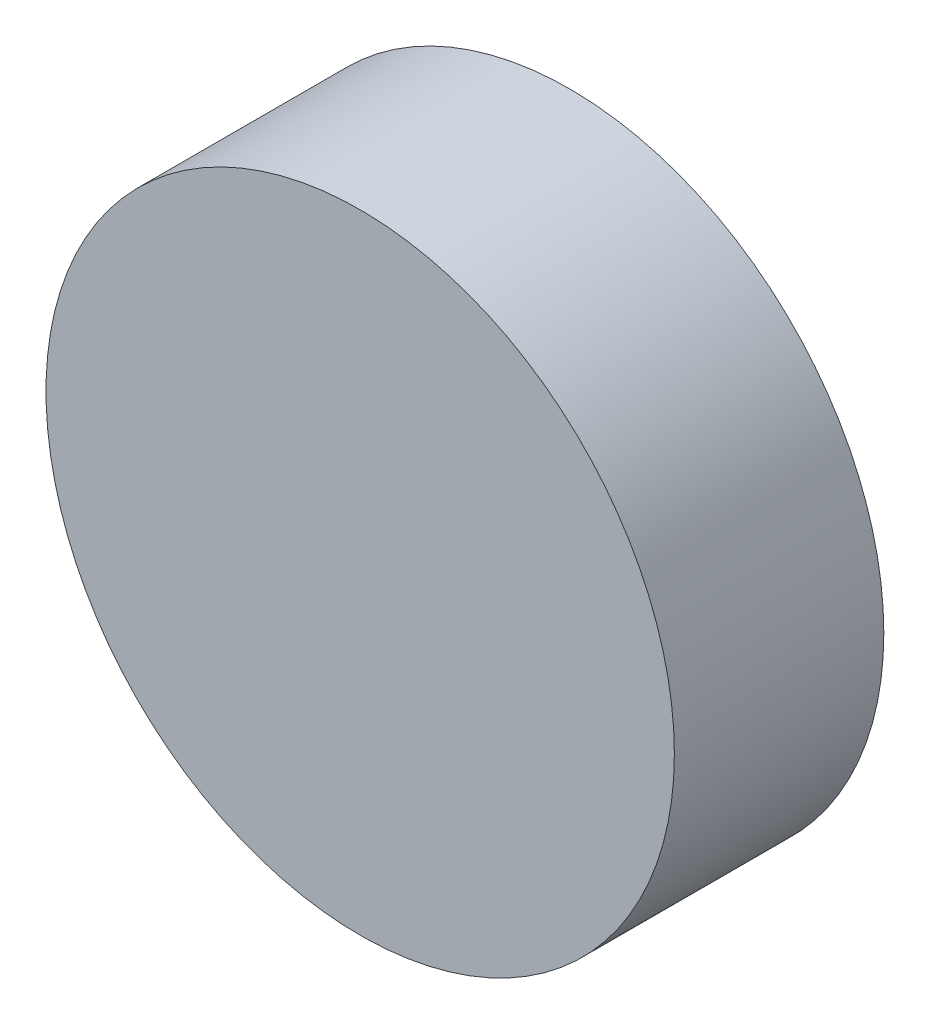
SolidWorks part; units mm, degrees
ref_plane "正面" through (0, 0, 0) normal (0, 0, 1) x (1, 0, 0)
ref_plane "平面" through (0, 0, 0) normal (0, 1, 0) x (1, 0, 0)
ref_plane "右側面" through (0, 0, 0) normal (1, 0, 0) x (0, 0, -1)
sketch "ｽｹｯﾁ1" plane through (0, 0, 0) normal (0, 0, 1) x (1, 0, 0)
  circle A0 centre (0, 0) radius 1.5
  dimension "D1" = 3
extrude "ﾎﾞｽ - 押し出し1" add sketch "ｽｹｯﾁ1" along normal blind 1
